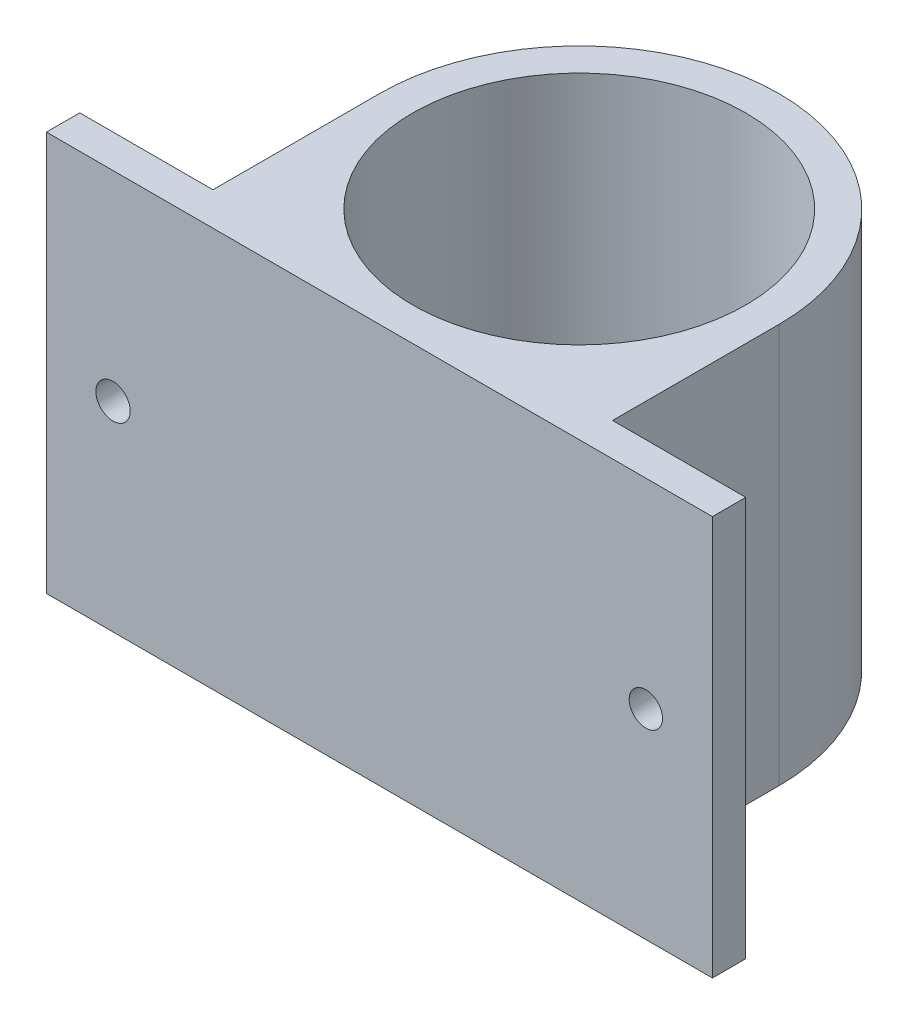
SolidWorks part; units mm, degrees
ref_plane "Front Plane" through (0, 0, 0) normal (0, 0, 1) x (1, 0, 0)
ref_plane "Top Plane" through (0, 0, 0) normal (0, 1, 0) x (1, 0, 0)
ref_plane "Right Plane" through (0, 0, 0) normal (1, 0, 0) x (0, 0, -1)
sketch "Sketch1" plane through (0, 0, 0) normal (0, 1, 0) x (1, 0, 0)
  line L0 (-63.5, -31.75) -> (-63.5, -38.1)
  line L1 (-63.5, -31.75) -> (63.5, -31.75)
  line L2 (0, -31.75) -> (0, -38.1)
  line L3 (-63.5, -38.1) -> (63.5, -38.1)
  line L4 (63.5, -31.75) -> (63.5, -38.1)
  line L5 (-38.1, 0) -> (-38.1, -31.75)
  line L6 (38.1, 0) -> (38.1, -31.75)
  circle A0 centre (0, 0) radius 31.75
  circle A1 centre (0, 0) radius 38.1
  dimension "D1" = 63.5
  dimension "D3" = 63.5
  dimension "D2" = 6.35
extrude "Boss-Extrude1" add sketch "Sketch1" along normal blind 76.2 contours L2 A1 L1 | L1 A1 L2 | A1 L3 L4 L1 | A1 L1 L0 L3 | A1 L5 L1 | L1 A1 A0 | A1 L1 L6
sketch "Sketch2" plane through (0, 0, 31.75) normal (0, 0, -1) x (-1, 0, 0)
  line L0 (-63.5, 38.1) -> (63.5, 38.1) construction
  line L1 (-63.5, 76.2) -> (-63.5, 0) construction
  line L2 (63.5, 76.2) -> (63.5, 0) construction
  line L3 (-50.8, 76.2) -> (-50.8, 0) construction
  line L4 (-38.1, 76.2) -> (-63.5, 76.2) construction
  line L5 (-38.1, 0) -> (-63.5, 0) construction
  line L6 (50.8, 76.2) -> (50.8, 0) construction
  line L7 (63.5, 76.2) -> (38.1, 76.2) construction
  line L8 (63.5, 0) -> (38.1, 0) construction
  circle A0 centre (50.8, 38.1) radius 3.2766
  circle A1 centre (-50.8, 38.1) radius 3.175
  dimension "D1" = 6.5532
  dimension "D2" = 6.35
extrude "Cut-Extrude1" cut sketch "Sketch2" against normal blind 50.8
